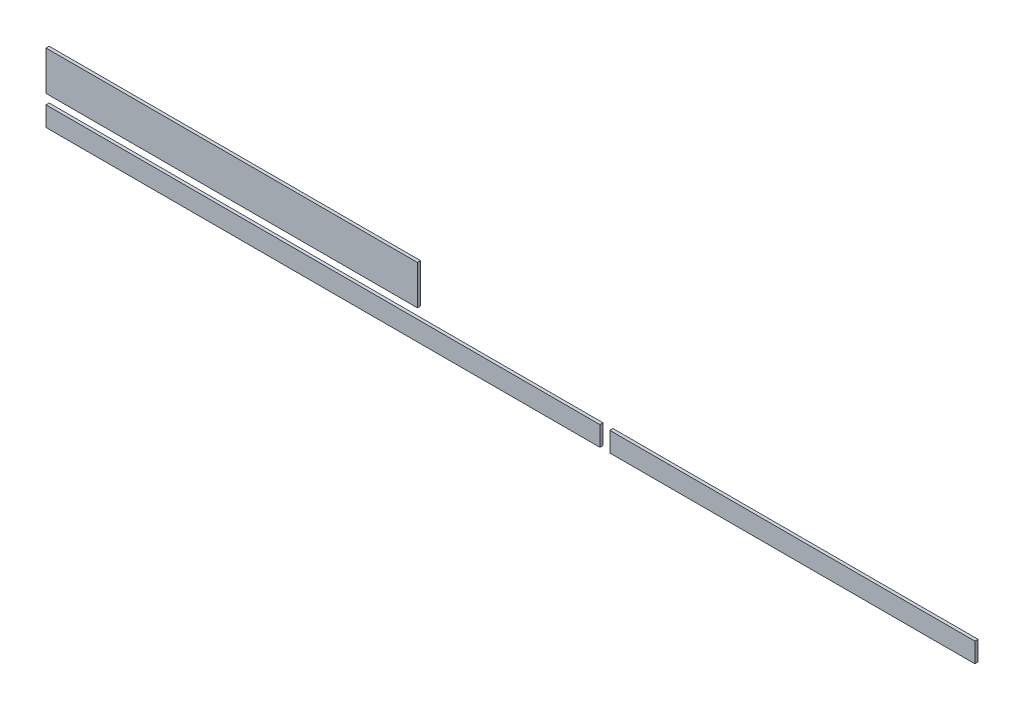
SolidWorks part; units mm, degrees
ref_plane "Front Plane" through (0, 0, 0) normal (0, 0, 1) x (1, 0, 0)
ref_plane "Top Plane" through (0, 0, 0) normal (0, 1, 0) x (1, 0, 0)
ref_plane "Right Plane" through (0, 0, 0) normal (1, 0, 0) x (0, 0, -1)
sketch "Sketch2" plane through (0, 0, 0) normal (0, 0, 1) x (1, 0, 0)
  line L1 (0, 10) -> (281.47, 10)
  line L2 (0, 10) -> (0, 0)
  line L3 (0, 0) -> (281.47, 0)
  line L4 (281.47, 10) -> (281.47, 0)
  line L5 (0, 10) -> (281.47, 0) construction
  line L6 (0, 0) -> (281.47, 10) construction
  line L7 (286.47, 0) -> (472, 0)
  line L8 (286.47, 0) -> (286.47, 10)
  line L9 (286.47, 10) -> (472, 10)
  line L10 (472, 0) -> (472, 10)
  line L11 (286.47, 0) -> (472, 10) construction
  line L12 (286.47, 10) -> (472, 0) construction
  line L13 (188.71, 15) -> (0, 15)
  line L14 (188.71, 15) -> (188.71, 35)
  line L15 (188.71, 35) -> (0, 35)
  line L16 (0, 15) -> (0, 35)
  line L17 (188.71, 15) -> (0, 35) construction
  line L18 (188.71, 35) -> (0, 15) construction
  point P0 (140.735, 5)
  point P5 (379.235, 5)
  point P10 (94.355, 25)
  point P15 (0, 0)
  point P17 (65.4069, 5)
  point P18 (15.6111, 24.4993)
  dimension "D1" = 10
  dimension "D2" = 281.47
  dimension "D3" = 5
  dimension "D4" = 185.53
  dimension "D5" = 5
  dimension "D6" = 20
  dimension "D7" = 188.71
extrude "Boss-Extrude1" add sketch "Sketch2" along normal blind 1.5875
